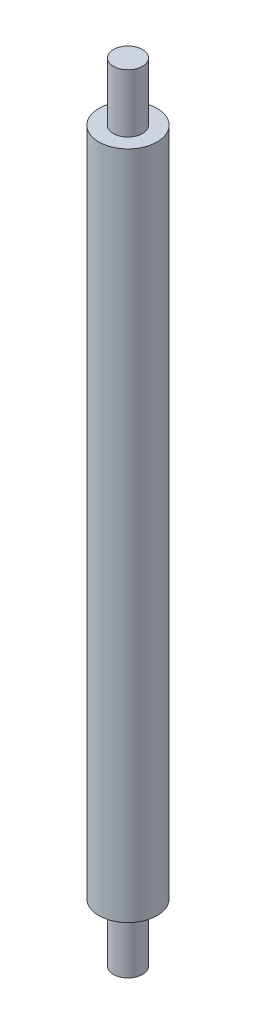
SolidWorks part; units mm, degrees
ref_plane "Front Plane" through (0, 0, 0) normal (0, 0, 1) x (1, 0, 0)
ref_plane "Top Plane" through (0, 0, 0) normal (0, 1, 0) x (1, 0, 0)
ref_plane "Right Plane" through (0, 0, 0) normal (1, 0, 0) x (0, 0, -1)
sketch "Sketch1" plane through (0, 0, 0) normal (0, 1, 0) x (1, 0, 0)
  circle A0 centre (-0.9513, -2.4621) radius 5
  dimension "D1" = 10
extrude "Boss-Extrude1" add sketch "Sketch1" along normal blind 115
sketch "Sketch2" plane through (0, 0, 0) normal (0, -1, 0) x (1, 0, 0)
  circle A0 centre (-0.9513, 2.4621) radius 2.5
  circle A1 centre (-0.9513, 2.4621) radius 5 construction
  dimension "D1" = 5
extrude "Boss-Extrude2" add sketch "Sketch2" along normal blind 10
ref_plane "Plane1" through (0, 57.5, 0) normal (0, 1, 0) x (1, 0, 0)
mirror "Mirror1" about plane through (0, 57.5, 0) normal (0, 1, 0) of "Boss-Extrude2"
